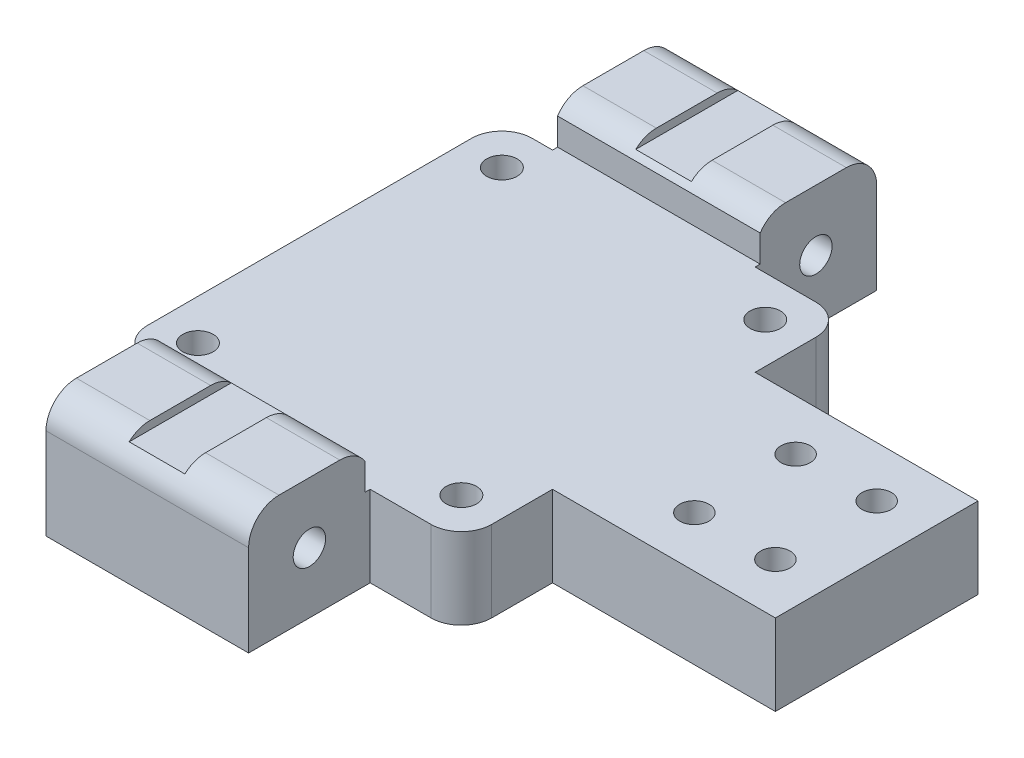
SolidWorks part; units mm, degrees
ref_plane "Front" through (0, 0, 0) normal (0, 0, 1) x (1, 0, 0)
ref_plane "Top" through (0, 0, 0) normal (0, 1, 0) x (1, 0, 0)
ref_plane "Right" through (0, 0, 0) normal (1, 0, 0) x (0, 0, -1)
sketch "Sketch1" plane through (0, 0, 0) normal (0, 1, 0) x (1, 0, 0)
  line L1 (0, 0) -> (300, 0)
  line L2 (0, 0) -> (0, -20)
  line L3 (0, -20) -> (300, -20)
  line L4 (300, 0) -> (300, -20)
  dimension "D1" = 20
  dimension "D2" = 300
extrude "Boss-Extrude1" add sketch "Sketch1" along normal blind 8
sketch "Sketch2" plane through (0, 0, 20) normal (0, 0, 1) x (1, 0, 0)
  line L0 (0, 8) -> (300, 8) construction
  line L1 (0, 0) -> (34, 0)
  line L2 (0, 0) -> (0, 8)
  line L3 (0, 8) -> (34, 8)
  line L4 (34, 0) -> (34, 8)
  line L5 (266, 8) -> (300, 8)
  line L6 (300, 0) -> (300, 8)
  line L7 (266, 0) -> (300, 0)
  line L8 (266, 0) -> (266, 8)
  dimension "D1" = 34
  dimension "D2" = 2
extrude "Boss-Extrude2" add sketch "Sketch2" along normal blind 9
sketch "Sketch3" plane through (0, 0, 0) normal (0, 0, -1) x (-1, 0, 0)
  line L0 (-300, 8) -> (0, 8) construction
  line L1 (0, 0) -> (-34, 0)
  line L2 (0, 0) -> (0, 8)
  line L3 (0, 8) -> (-34, 8)
  line L4 (-34, 0) -> (-34, 8)
  line L5 (-300, 0) -> (-300, 8)
  line L6 (-266, 8) -> (-300, 8)
  line L7 (-266, 0) -> (-266, 8)
  line L8 (-266, 0) -> (-300, 0)
  dimension "D1" = 34
  dimension "D2" = 2
extrude "Boss-Extrude3" add sketch "Sketch3" along normal blind 9
sketch "Sketch4" plane through (0, 8, 0) normal (0, 1, 0) x (1, 0, 0)
  line L0 (0, 9) -> (34, 9) construction
  line L1 (0, 9) -> (0, -29) construction
  circle A0 centre (4, 5) radius 1.5
  circle A1 centre (30, 5) radius 1.5
  circle A2 centre (30, -25) radius 1.5
  circle A3 centre (4, -25) radius 1.5
  circle A4 centre (296, -25) radius 1.5
  circle A5 centre (296, 5) radius 1.5
  circle A6 centre (270, -25) radius 1.5
  circle A7 centre (270, 5) radius 1.5
  dimension "D1" = 3
  dimension "D2" = 4
  dimension "D3" = 4
  dimension "D4" = 2
  dimension "D5" = 2
  dimension "D6" = 2
extrude "Cut-Extrude1" cut sketch "Sketch4" against normal through all
sketch "Sketch5" plane through (0, 0, 20) normal (0, 0, 1) x (1, 0, 0)
  line L0 (34, 8) -> (266, 8) construction
  line L1 (266, 0) -> (241, 0)
  line L2 (266, 0) -> (266, 8)
  line L3 (266, 8) -> (241, 8)
  line L4 (241, 0) -> (241, 8)
  dimension "D1" = 25
extrude "Boss-Extrude4" add sketch "Sketch5" along normal blind 17
sketch "Sketch6" plane through (0, 0, 0) normal (0, 0, -1) x (-1, 0, 0)
  line L0 (-266, 0) -> (-34, 0) construction
  line L1 (-266, 8) -> (-241, 8)
  line L2 (-266, 8) -> (-266, 0)
  line L3 (-266, 0) -> (-241, 0)
  line L4 (-241, 8) -> (-241, 0)
  dimension "D1" = 25
extrude "Boss-Extrude5" add sketch "Sketch6" along normal blind 17
sketch "Sketch7" plane through (0, 8, 0) normal (0, 1, 0) x (1, 0, 0)
  line L0 (266, -37) -> (241, -37) construction
  line L1 (259, -29) -> (249, -29)
  line L2 (259, -29) -> (259, 9)
  line L3 (259, 9) -> (249, 9)
  line L4 (249, -29) -> (249, 9)
  line L5 (241, -37) -> (241, -20) construction
  dimension "D1" = 10
  dimension "D2" = 38
  dimension "D3" = 8
  dimension "D4" = 8
extrude "Cut-Extrude2" cut sketch "Sketch7" against normal through all
sketch "Sketch8" plane through (0, 8, 0) normal (0, 1, 0) x (1, 0, 0)
  line L0 (259, -29) -> (259, 9) construction
  line L1 (259, -18) -> (266, -18)
  line L2 (259, -18) -> (259, -2)
  line L3 (259, -2) -> (266, -2)
  line L4 (266, -18) -> (266, -2)
  line L5 (266, -37) -> (241, -37) construction
  dimension "D1" = 7
  dimension "D2" = 16
  dimension "D3" = 19
extrude "Cut-Extrude3" cut sketch "Sketch8" against normal blind 4
sketch "Sketch9" plane through (259, 0, 0) normal (-1, 0, 0) x (0, 0, 1)
  line L0 (18, 4) -> (22, 8)
  line L1 (29, 8) -> (18, 8) construction
  line L2 (22, 8) -> (18, 8)
  line L3 (18, 8) -> (18, 4)
  line L4 (2, 4) -> (-2, 8)
  line L5 (2, 8) -> (-9, 8) construction
  line L6 (-2, 8) -> (2, 8)
  line L7 (2, 8) -> (2, 4)
  dimension "D1" = 4
  dimension "D2" = 4
extrude "Cut-Extrude4" cut sketch "Sketch9" against normal blind 7
sketch "Sketch10" plane through (259, 0, 0) normal (-1, 0, 0) x (0, 0, 1)
  line L0 (-9, 8) -> (-2, 0)
  line L1 (29, 0) -> (-9, 0) construction
  line L2 (-2, 0) -> (-9, 0)
  line L3 (-9, 0) -> (-9, 8)
  line L4 (29, 8) -> (22, 0)
  line L5 (22, 0) -> (29, 0)
  line L6 (29, 0) -> (29, 8)
  line L7 (-51.4523, 12.1971) -> (-51.8778, 12.5861)
  line M6 (-9, 8) -> (-9, 0)
  line M7 (-9, 0) -> (29, 0)
  line M8 (29, 0) -> (29, 8)
  dimension "D1" = 7
  dimension "D2" = 7
extrude "Boss-Extrude6" add sketch "Sketch10" along normal blind 10 contours L0 M6 M7 | L4 M8 M7
sketch "Sketch12" plane through (0, 0, 37) normal (0, 0, 1) x (1, 0, 0)
  line L0 (241, 0) -> (266, 0) construction
  line L1 (241, 8) -> (249, 8)
  line L2 (241, 8) -> (241, 0)
  line L3 (241, 0) -> (249, 0)
  line L4 (249, 8) -> (249, 0)
  dimension "D1" = 8
extrude "Boss-Extrude7" add sketch "Sketch12" along normal blind 17
sketch "Sketch13" plane through (0, 8, 0) normal (0, 1, 0) x (1, 0, 0)
  line L0 (249, -54) -> (241, -54) construction
  line L1 (249, -54) -> (249, -37) construction
  circle A0 centre (245, -50) radius 1.7
  circle A1 centre (245, -18) radius 1.7
  dimension "D1" = 3.4
  dimension "D2" = 4
  dimension "D3" = 4
  dimension "D4" = 2
extrude "Cut-Extrude6" cut sketch "Sketch13" against normal through all
sketch "Sketch14" plane through (0, 0, 29) normal (0, 0, 1) x (1, 0, 0)
  line L1 (295, 13) -> (275, 13)
  line L2 (295, 13) -> (295, 0)
  line L3 (295, 0) -> (275, 0)
  line L4 (275, 13) -> (275, 0)
  line L5 (266, 0) -> (300, 0) construction
  line L7 (266, 8) -> (266, 0) construction
  dimension "D1" = 20
  dimension "D2" = 9
  dimension "D3" = 13
extrude "Boss-Extrude8" add sketch "Sketch14" along normal blind 12
sketch "Sketch15" plane through (295, 0, 0) normal (1, 0, 0) x (0, 0, -1)
  line L0 (-41, 0) -> (-41, 13) construction
  line L1 (-41, 13) -> (-29, 13) construction
  circle A0 centre (-35, 8) radius 1.6
  dimension "D1" = 3.2
  dimension "D2" = 6
  dimension "D3" = 5
extrude "Cut-Extrude7" cut sketch "Sketch15" against normal blind 20
sketch "Sketch16" plane through (0, 0, -9) normal (0, 0, -1) x (-1, 0, 0)
  line L1 (-295, 13) -> (-275, 13)
  line L2 (-295, 13) -> (-295, 0)
  line L3 (-295, 0) -> (-275, 0)
  line L4 (-275, 13) -> (-275, 0)
  line L5 (-300, 0) -> (-266, 0) construction
  line L6 (-266, 0) -> (-266, 8) construction
  dimension "D1" = 20
  dimension "D2" = 9
  dimension "D3" = 13
extrude "Boss-Extrude9" add sketch "Sketch16" along normal blind 12
sketch "Sketch17" plane through (295, 0, 0) normal (1, 0, 0) x (0, 0, -1)
  line L1 (21, 13) -> (21, 0) construction
  line L2 (21, 13) -> (9, 13) construction
  circle A0 centre (15, 8) radius 1.6
  dimension "D1" = 3.2
  dimension "D2" = 5
  dimension "D3" = 6
extrude "Cut-Extrude8" cut sketch "Sketch17" against normal blind 20
sketch "Sketch18" plane through (0, 0, -9) normal (0, 0, -1) x (-1, 0, 0)
  line L1 (-25, 12) -> (-5, 12)
  line L2 (-25, 12) -> (-25, 0)
  line L3 (-25, 0) -> (-5, 0)
  line L4 (-5, 12) -> (-5, 0)
  line L5 (-34, 0) -> (0, 0) construction
  line L6 (-34, 8) -> (-34, 0) construction
  dimension "D1" = 20
  dimension "D2" = 9
  dimension "D3" = 12
extrude "Boss-Extrude10" add sketch "Sketch18" along normal blind 12
sketch "Sketch19" plane through (5, 0, 0) normal (-1, 0, 0) x (0, 0, 1)
  line L0 (-21, 0) -> (-21, 12) construction
  line L1 (-21, 12) -> (-9, 12) construction
  circle A0 centre (-15, 6) radius 1.6
  dimension "D1" = 3.2
  dimension "D2" = 6
  dimension "D3" = 6
extrude "Cut-Extrude9" cut sketch "Sketch19" against normal blind 20
sketch "Sketch20" plane through (0, 0, 29) normal (0, 0, 1) x (1, 0, 0)
  line L1 (5, 12) -> (25, 12)
  line L2 (5, 12) -> (5, 0)
  line L3 (5, 0) -> (25, 0)
  line L4 (25, 12) -> (25, 0)
  line L5 (0, 0) -> (34, 0) construction
  line L6 (34, 0) -> (34, 8) construction
  dimension "D1" = 20
  dimension "D2" = 9
  dimension "D3" = 12
extrude "Boss-Extrude11" add sketch "Sketch20" along normal blind 12
sketch "Sketch21" plane through (5, 0, 0) normal (-1, 0, 0) x (0, 0, 1)
  line L0 (41, 12) -> (41, 0) construction
  line L2 (41, 12) -> (29, 12) construction
  circle A0 centre (35, 6) radius 1.6
  dimension "D1" = 3.2
  dimension "D2" = 6
  dimension "D3" = 6
extrude "Cut-Extrude10" cut sketch "Sketch21" against normal blind 20
fillet "Fillet6" radius 3 8 edges at (15, 12, 41) (15, 12, 29) (15, 12, -9) (15, 12, -21) (285, 13, 41) (285, 13, 29) (285, 13, -9) (285, 13, -21)
sketch "Sketch22" plane through (300, 0, 0) normal (1, 0, 0) x (0, 0, -1)
  line L1 (-72.0035, 35.0177) -> (51.7473, 35.0177)
  line L2 (-72.0035, 35.0177) -> (-72.0035, -37.6215)
  line L3 (-72.0035, -37.6215) -> (51.7473, -37.6215)
  line L4 (51.7473, 35.0177) -> (51.7473, -37.6215)
extrude "Cut-Extrude11" cut sketch "Sketch22" against normal blind 244
sketch "Sketch23" plane through (0, 0, 0) normal (0, -1, 0) x (-1, 0, 0)
  line L0 (-34, -20) -> (-56, -20) construction
  line L1 (-56, -20) -> (-56, 0) construction
  line L2 (-56, 0) -> (-34, 0) construction
  circle A0 centre (-51, -5) radius 1.45
  circle A1 centre (-51, -15) radius 1.45
  circle A2 centre (-43, -5) radius 1.45
  circle A3 centre (-43, -15) radius 1.45
  dimension "D1" = 2.9
  dimension "D2" = 2.9
  dimension "D3" = 2.9
  dimension "D4" = 2.9
  dimension "D5" = 5
  dimension "D6" = 5
  dimension "D7" = 5
  dimension "D8" = 5
  dimension "D9" = 5
  dimension "D10" = 8
  dimension "D11" = 8
  dimension "D12" = 5
extrude "Cut-Extrude12" cut sketch "Sketch23" against normal through all
fillet "Fillet7" radius 3 4 edges at (0, 4, 29) (0, 4, -9) (34, 4, 29) (34, 4, -9)
sketch "Sketch24" plane through (0, 12, 0) normal (0, 1, 0) x (1, 0, 0)
  line L0 (5, 18) -> (5, 12) construction
  line L1 (12.25, 29.5448) -> (17.75, 29.5448)
  line L2 (12.25, 29.5448) -> (12.25, -48.6988)
  line L3 (12.25, -48.6988) -> (17.75, -48.6988)
  line L4 (17.75, 29.5448) -> (17.75, -48.6988)
  dimension "D1" = 5.5
  dimension "D2" = 7.25
extrude "Cut-Extrude13" cut sketch "Sketch24" against normal blind 0.8
sketch "Sketch25" plane through (0, 0, 29) normal (0, 0, -1) x (-1, 0, 0)
  line L1 (-25, 8) -> (-5, 8)
  line L2 (-25, 8) -> (-25, 13.7566)
  line L3 (-25, 13.7566) -> (-5, 13.7566)
  line L4 (-5, 8) -> (-5, 13.7566)
  dimension "D1" = 20
extrude "Cut-Extrude14" cut sketch "Sketch25" against normal blind 0.5
sketch "Sketch26" plane through (0, 0, -9) normal (0, 0, 1) x (1, 0, 0)
  line L1 (5, 8) -> (25, 8)
  line L2 (5, 8) -> (5, 29.4591)
  line L3 (5, 29.4591) -> (25, 29.4591)
  line L4 (25, 8) -> (25, 29.4591)
  dimension "D1" = 20
extrude "Cut-Extrude15" cut sketch "Sketch26" against normal blind 0.5
